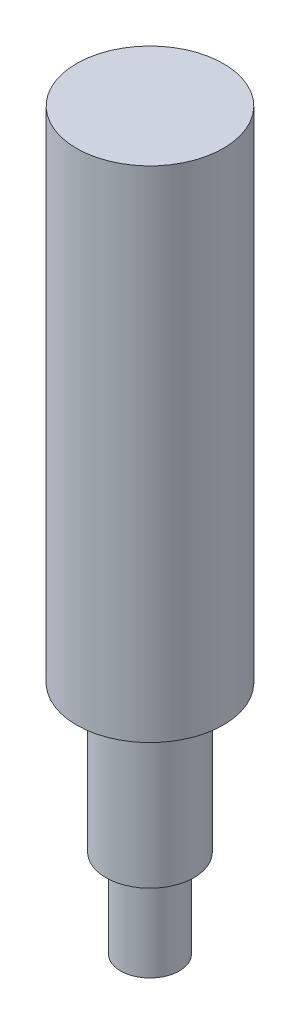
SolidWorks part; units mm, degrees
ref_plane "Front Plane" through (0, 0, 0) normal (0, 0, 1) x (1, 0, 0)
ref_plane "Top Plane" through (0, 0, 0) normal (0, 1, 0) x (1, 0, 0)
ref_plane "Right Plane" through (0, 0, 0) normal (1, 0, 0) x (0, 0, -1)
sketch3d "M4 Thread Blank Sketch datum points"
  point P0 (0, -140, 0)
  point P1 (10, -140, 0)
  point P2 (0, -140, -10)
ref_plane "M4 Thread Blank Sketch plane" through (0, -140, 0) normal (0, 1, 0) x (1, 0, 0)
sketch "M4 Thread Blank Sketch" plane through (0, -140, 0) normal (0, 1, 0) x (1, 0, 0)
  circle A0 centre (-20.2917, 0) radius 2
extrude "M4 Thread Blank" add sketch "M4 Thread Blank Sketch" along normal blind 6 separate body
sketch3d "Locating Spigot Sketch datum points"
  point P0 (0, -134, 0)
  point P1 (10, -134, 0)
  point P2 (0, -134, -10)
ref_plane "Locating Spigot Sketch plane" through (0, -134, 0) normal (0, 1, 0) x (1, 0, 0)
sketch "Locating Spigot Sketch" plane through (0, -134, 0) normal (0, 1, 0) x (1, 0, 0)
  circle A0 centre (-20.2917, 0) radius 3
extrude "Locating Spigot" add sketch "Locating Spigot Sketch" along normal blind 10
sketch3d "Guide Shoulder Sketch datum points"
  point P0 (0, -124, 0)
  point P1 (10, -124, 0)
  point P2 (0, -124, -10)
ref_plane "Guide Shoulder Sketch plane" through (0, -124, 0) normal (0, 1, 0) x (1, 0, 0)
sketch "Guide Shoulder Sketch" plane through (0, -124, 0) normal (0, 1, 0) x (1, 0, 0)
  circle A0 centre (-20.2917, 0) radius 5
extrude "Guide Shoulder" add sketch "Guide Shoulder Sketch" along normal blind 34
